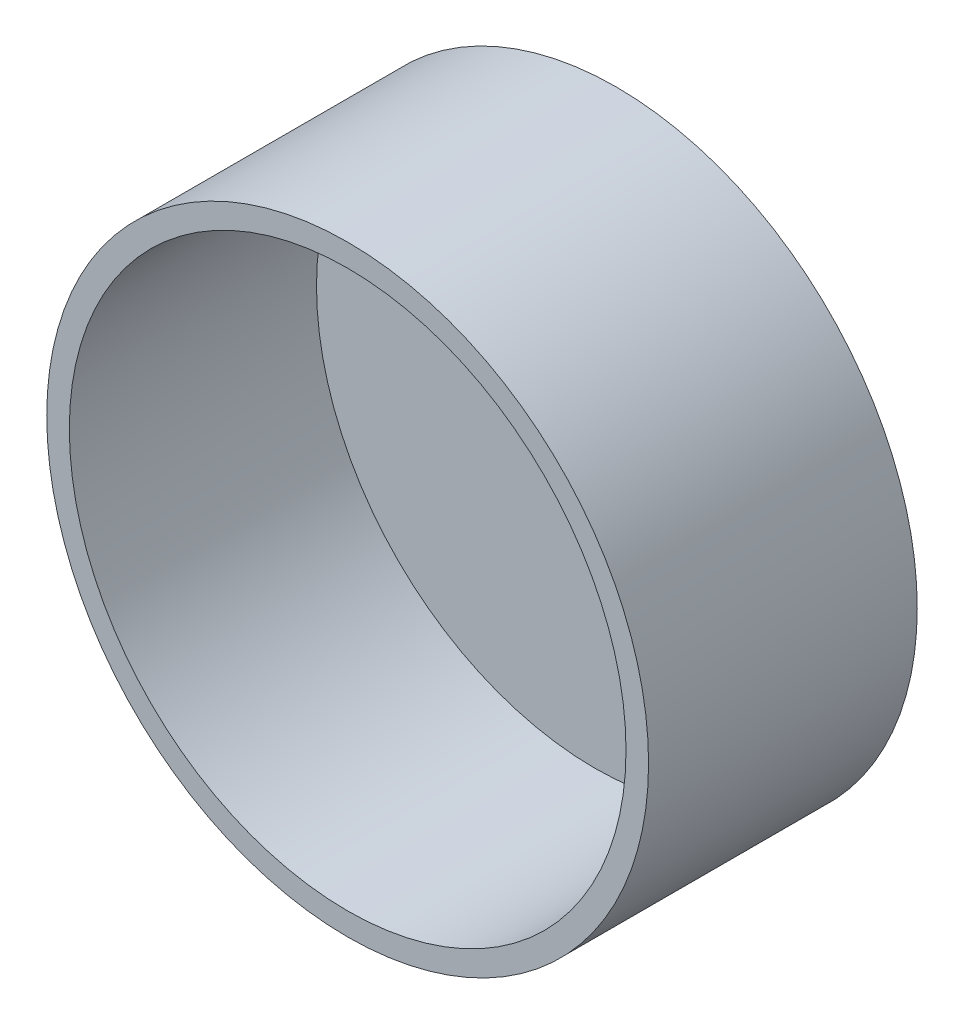
SolidWorks part; units mm, degrees
material "ABS"
ref_plane "Plan de face" through (0, 0, 0) normal (0, 0, 1) x (1, 0, 0)
ref_plane "Plan de dessus" through (0, 0, 0) normal (0, 1, 0) x (1, 0, 0)
ref_plane "Plan de droite" through (0, 0, 0) normal (1, 0, 0) x (0, 0, -1)
sketch "Esquisse1" plane through (0, 0, 0) normal (0, 0, 1) x (1, 0, 0)
  circle A0 centre (0, 0) radius 14
  dimension "D1" = 28
extrude "Boss.-Extru.1" add sketch "Esquisse1" along normal blind 1
sketch "Esquisse2" plane through (0, 0, 1) normal (0, 0, 1) x (1, 0, 0)
  circle A0 centre (0, 0) radius 12.95
  circle A1 centre (0, 0) radius 14
  dimension "D1" = 25.9
extrude "Boss.-Extru.2" add sketch "Esquisse2" along normal blind 11.5
